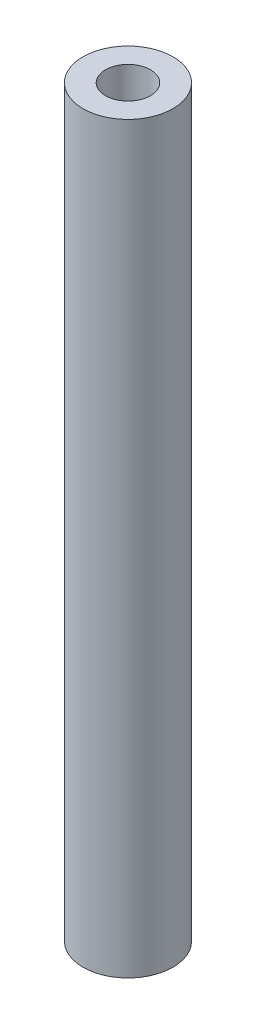
SolidWorks part; units mm, degrees
ref_plane "Front Plane" through (0, 0, 0) normal (0, 0, 1) x (1, 0, 0)
ref_plane "Top Plane" through (0, 0, 0) normal (0, 1, 0) x (1, 0, 0)
ref_plane "Right Plane" through (0, 0, 0) normal (1, 0, 0) x (0, 0, -1)
sketch "Sketch1" plane through (0, 0, 0) normal (0, 1, 0) x (1, 0, 0)
  circle A0 centre (0, 0) radius 3.75
  circle A1 centre (0, 0) radius 1.875
  dimension "D1" = 3.75
  dimension "D2" = 7.5
extrude "Boss-Extrude1" add sketch "Sketch1" along normal blind 62
